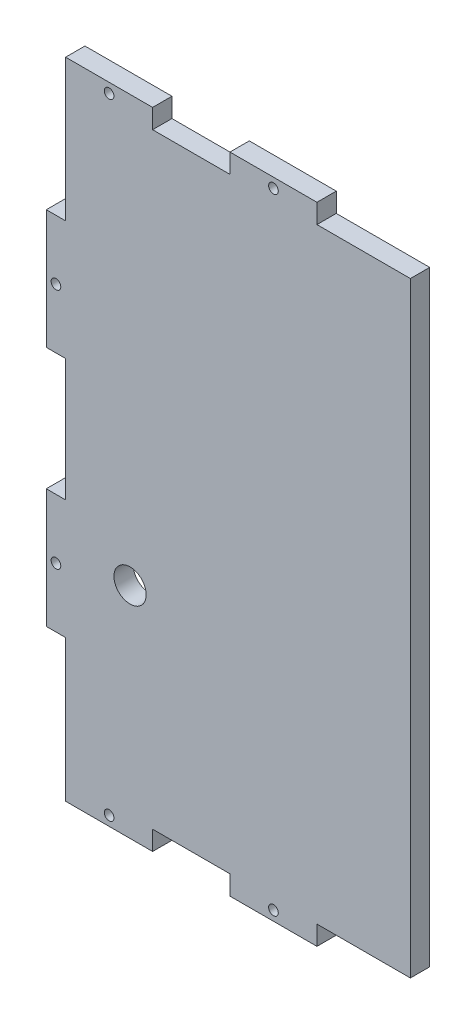
SolidWorks part; units mm, degrees
ref_plane "Plan de face" through (0, 0, 0) normal (0, 0, 1) x (1, 0, 0)
ref_plane "Plan de dessus" through (0, 0, 0) normal (0, 1, 0) x (1, 0, 0)
ref_plane "Plan de droite" through (0, 0, 0) normal (1, 0, 0) x (0, 0, -1)
sketch "Esquisse1" plane through (0, 0, 0) normal (0, 0, 1) x (1, 0, 0)
  line L1 (0, 0) -> (-143, 0)
  line L2 (0, 0) -> (0, 200)
  line L3 (0, 200) -> (-143, 200)
  line L4 (-143, 0) -> (-143, 200)
  dimension "D1" = 200
  dimension "D2" = 143
extrude "Boss.-Extru.1" add sketch "Esquisse1" along normal blind 6
sketch "Esquisse2" plane through (0, 0, 0) normal (0, 0, -1) x (-1, 0, 0)
  line L0 (0, 0) -> (0, 200) construction
  line L1 (0, 50) -> (6, 50)
  line L2 (0, 50) -> (0, 80)
  line L3 (0, 80) -> (6, 80)
  line L4 (6, 50) -> (6, 80)
  line L5 (143, 0) -> (0, 0) construction
  line L6 (0, 120) -> (6, 120)
  line L7 (0, 120) -> (0, 150)
  line L8 (0, 150) -> (6, 150)
  line L9 (6, 120) -> (6, 150)
  line L11 (0, 200) -> (143, 200) construction
  line L12 (36, 0) -> (65, 0)
  line L13 (36, 0) -> (36, 6)
  line L14 (36, 6) -> (65, 6)
  line L15 (65, 0) -> (65, 6)
  line L16 (92, 0) -> (116, 0)
  line L17 (92, 0) -> (92, 6)
  line L18 (92, 6) -> (116, 6)
  line L19 (116, 0) -> (116, 6)
  line L20 (36, 200) -> (65, 200)
  line L21 (36, 200) -> (36, 194)
  line L22 (36, 194) -> (65, 194)
  line L23 (65, 200) -> (65, 194)
  line L25 (92, 200) -> (116, 200)
  line L26 (92, 200) -> (92, 194)
  line L27 (92, 194) -> (116, 194)
  line L28 (116, 200) -> (116, 194)
  dimension "D1" = 30
  dimension "D2" = 30
  dimension "D3" = 6
  dimension "D4" = 6
  dimension "D5" = 40
  dimension "D6" = 50
  dimension "D7" = 27
  dimension "D8" = 29
  dimension "D9" = 24
  dimension "D10" = 6
  dimension "D11" = 6
  dimension "D12" = 27
  dimension "D13" = 27
  dimension "D14" = 29
  dimension "D15" = 27
  dimension "D16" = 24
  dimension "D17" = 6
  dimension "D18" = 6
extrude "Enlèv. mat.-Extru.1" cut sketch "Esquisse2" against normal blind 6
sketch "Esquisse3" plane through (-143, 0, 0) normal (-1, 0, 0) x (0, 0, 1)
  line L0 (0, 200) -> (0, 0) construction
  line L1 (0, 44) -> (6, 44)
  line L2 (0, 44) -> (0, 81)
  line L3 (0, 81) -> (6, 81)
  line L4 (6, 44) -> (6, 81)
  line L5 (6, 200) -> (6, 0) construction
  line L7 (0, 119) -> (6, 119)
  line L8 (0, 119) -> (0, 156)
  line L9 (0, 156) -> (6, 156)
  line L10 (6, 119) -> (6, 156)
  dimension "D1" = 38
  dimension "D2" = 37
  dimension "D3" = 37
  dimension "D4" = 44
extrude "Boss.-Extru.2" add sketch "Esquisse3" along normal blind 6
sketch "Esquisse4" plane through (0, 0, 0) normal (0, 0, -1) x (-1, 0, 0)
  line L1 (36, 0) -> (0, 0)
  line L2 (36, 0) -> (36, 200)
  line L3 (36, 200) -> (0, 200)
  line L4 (0, 0) -> (0, 200)
extrude "Enlèv. mat.-Extru.2" cut sketch "Esquisse4" against normal blind 10
sketch "Esquisse5" plane through (0, 0, 0) normal (0, 0, -1) x (-1, 0, 0)
  line L0 (92, 0) -> (65, 0) construction
  line L1 (149, 81) -> (149, 44) construction
  line L2 (116, 0) -> (116, 6) construction
  line L3 (65, 194) -> (65, 200) construction
  line L4 (149, 81) -> (143, 81) construction
  line L5 (149, 156) -> (143, 156) construction
  line L6 (65, 200) -> (92, 200) construction
  circle A0 centre (78.5, 3) radius 2.995
  circle A1 centre (129.5, 3) radius 2.995
  circle A2 centre (78.5, 197) radius 2.995
  circle A3 centre (129.5, 197) radius 2.995
  circle A4 centre (146, 62.5) radius 2.995
  circle A5 centre (146, 137.5) radius 2.995
  point P21 (146, 81)
  point P24 (146, 156)
  dimension "D1" = 5.99
  dimension "D4" = 5.99
  dimension "D6" = 5.99
  dimension "D8" = 5.99
  dimension "D9" = 5.99
  dimension "D11" = 5.99
  dimension "D2" = 3
  dimension "D3" = 13.5
  dimension "D5" = 13.5
  dimension "D7" = 13.5
  dimension "D10" = 3
  dimension "D12" = 18.5
  dimension "D13" = 18.5
  dimension "D14" = 3
  dimension "D15" = 0
extrude "Enlèv. mat.-Extru.3" cut sketch "Esquisse5" against normal blind 3
sketch "Esquisse6" plane through (0, 0, 0) normal (0, 0, -1) x (-1, 0, 0)
  circle A0 centre (78.5, 3) radius 1.5
  circle A1 centre (129.5, 3) radius 1.5
  circle A2 centre (78.5, 197) radius 1.5
  circle A3 centre (129.5, 197) radius 1.5
  circle A4 centre (146, 62.5) radius 1.5
  circle A5 centre (146, 137.5) radius 1.5
extrude "Enlèv. mat.-Extru.4" cut sketch "Esquisse6" against normal blind 6
sketch "Esquisse7" plane through (0, 0, 0) normal (0, 0, -1) x (-1, 0, 0)
  line L1 (143, 119) -> (143, 81) construction
  line L2 (116, 6) -> (92, 6) construction
  circle A0 centre (123, 68) radius 5
  dimension "D1" = 10
  dimension "D2" = 62
  dimension "D3" = 20
extrude "Enlèv. mat.-Extru.5" cut sketch "Esquisse7" against normal blind 10
